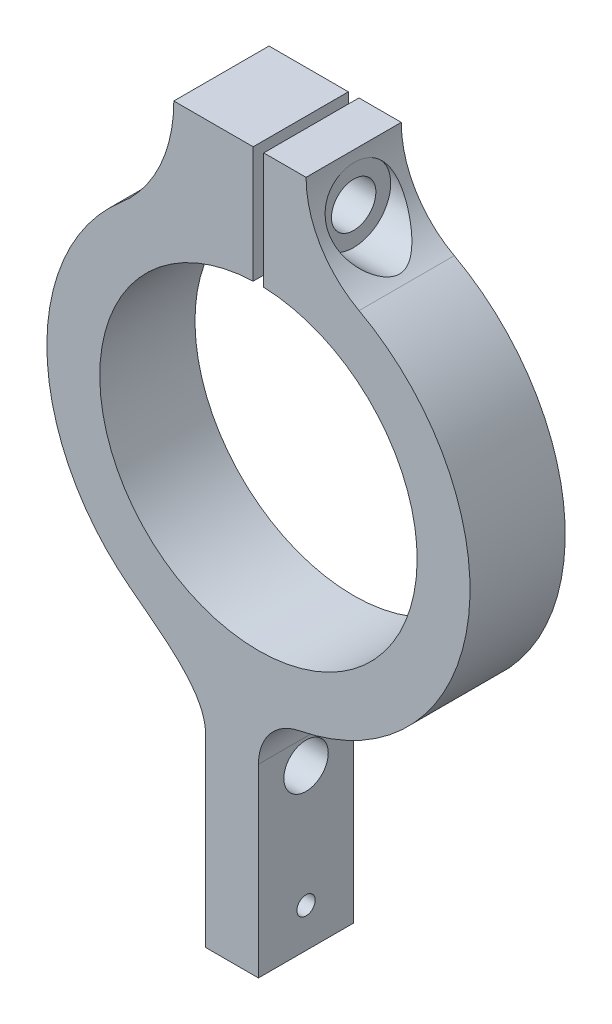
SolidWorks part; units mm, degrees
material "6061-T6 (SS)"
ref_plane "Front Plane" through (0, 0, 0) normal (0, 0, 1) x (1, 0, 0)
ref_plane "Top Plane" through (0, 0, 0) normal (0, 1, 0) x (1, 0, 0)
ref_plane "Right Plane" through (0, 0, 0) normal (1, 0, 0) x (0, 0, -1)
sketch "Sketch1" plane through (0, 0, 0) normal (0, 0, 1) x (1, 0, 0)
  line L0 (0, 0) -> (0, 40) construction
  line L1 (0, -48.6004) -> (0, -83.6004)
  line L2 (0, -83.6004) -> (-10, -83.6004)
  line L3 (-10, -83.6004) -> (-10, -48.6004)
  line L4 (30, 0) -> (40, 0) construction
  line L6 (0, 40) -> (0, 52) construction
  line L7 (0, 52) -> (1, 52) construction
  line L8 (1, 52) -> (1, 29.9833)
  line L9 (1, 52) -> (9, 52)
  line L11 (0, 52) -> (-1, 52) construction
  line L12 (-1, 52) -> (-1, 29.9833)
  line L13 (-1, 52) -> (-16, 52)
  arc A0 (-1, 29.9833) -> (1, 29.9833) centre (0, 0) ccw
  arc A1 (0, -48.6004) -> (7.6931, -39.2532) centre (9.525, -48.6004) cw
  arc A2 (0, 40) -> (-1, 39.9875) centre (0, 0) ccw construction
  arc A3 (9, 52) -> (19.0232, 35.1869) centre (28.1129, 52) ccw
  arc A4 (-25.9512, 30.439) -> (-26.5352, -29.9313) centre (0, 0) ccw
  circle A5 centre (0, 0) radius 40 construction
  arc A6 (-25.9512, 30.439) -> (-16, 52) centre (-44.3333, 52) ccw
  arc A8 (7.6931, -39.2532) -> (19.0232, 35.1869) centre (0, 0) ccw
  spline S0 degree 3 poles (-26.5352, -29.9313) (-20.9482, -34.8844) (-10, -40.904) (-10, -48.6004) knots 0 0 0 0 1 1 1 1
  point P27 (0, -40)
  dimension "D1" = 60
  dimension "D3" = 35
  dimension "D4" = 10
  dimension "D2" = 10
  dimension "D11" = 9.525
  dimension "D6" = 12
  dimension "D7" = 1
  dimension "D8" = 8
  dimension "D9" = 1
  dimension "D10" = 15
extrude "main body" add sketch "Sketch1" along normal blind 18
sketch "Sketch7" plane through (1, 0, 0) normal (-1, 0, 0) x (0, 0, 1)
  line L3 (9, 43) -> (9, 52) construction
  line L4 (18, 52) -> (0, 52) construction
  line L5 (9, 43) -> (0, 43) construction
  line L6 (0, 52) -> (0, 35.1869) construction
  circle A0 centre (9, 43) radius 4
  dimension "D1" = 8
sketch "Sketch12" plane through (0, 0, 0) normal (1, 0, 0) x (0, 0, -1)
  circle A0 centre (-9, -53.34) radius 4
  circle A1 centre (-9, -53.34) radius 7 construction
  circle A2 centre (-9, -76.2) radius 4
  circle A3 centre (-9, -76.2) radius 7 construction
  dimension "D1" = 8
  dimension "D2" = 14
  dimension "D3" = 14
  dimension "D4" = 8
  dimension "D6" = 22.86
  dimension "D5" = 76.2
hole_wizard "M8 Clearance Hole1" positions "Sketch13" profile "Sketch14" hole size "M8" standard "ANSI Metric"
sketch "Sketch13" plane through (1, 0, 0) normal (-1, 0, 0) x (0, 0, 1)
  point P0 (9, 43)
sketch "Sketch14" plane through (1, 43, 9) normal (0, 1, 0) x (0, 0, 1)
  line L0 (0, 0) -> (0, 39)
  line L1 (0, 39) -> (4.2, 39)
  line L2 (4.2, 39) -> (4.2, 0)
  line L5 (4.2, 0) -> (0, 0)
  line L11 (0, -6.35) -> (0, 107.95) construction
  dimension "Thru Hole Dia." = 8.4
  dimension "Thru Hole Depth" = 39
hole_wizard "M8 Clearance Hole2" positions "Sketch15" profile "Sketch16" hole size "M8" standard "ANSI Metric" end condition through all
sketch "Sketch15" plane through (1, 0, 0) normal (-1, 0, 0) x (0, 0, 1)
  point P0 (9, 43)
sketch "Sketch16" plane through (1, 43, 9) normal (0, 1, 0) x (0, 0, -1)
  line L0 (0, 0) -> (0, 41)
  line L1 (0, 41) -> (4.2, 41)
  line L2 (4.2, 41) -> (4.2, 0)
  line L5 (4.2, 0) -> (0, 0)
  line L11 (0, -6.35) -> (0, 107.95) construction
  dimension "Thru Hole Dia." = 8.4
  dimension "Thru Hole Depth" = 41
sketch "Sketch17" plane through (0, 0, 18) normal (0, 0, 1) x (1, 0, 0)
  line L0 (-16, 52) -> (-16, 25.3772)
  line L1 (9, 52) -> (9, 28.6182)
  arc A0 (-1, 29.9833) -> (1, 29.9833) centre (0, 0) ccw construction
hole_wizard "M8 Clearance Hole3" positions "Sketch18" profile "Sketch19" hole size "M8" standard "ANSI Metric" end condition through all
sketch "Sketch18" plane through (0, 0, 0) normal (1, 0, 0) x (0, 0, -1)
  point P0 (-9, -53.34)
sketch "Sketch19" plane through (0, -53.34, 9) normal (0, 1, 0) x (0, 0, -1)
  line L0 (0, 0) -> (0, 40)
  line L1 (0, 40) -> (4.2, 40)
  line L2 (4.2, 40) -> (4.2, 0)
  line L5 (4.2, 0) -> (0, 0)
  line L11 (0, -6.35) -> (0, 107.95) construction
  dimension "Thru Hole Dia." = 8.4
  dimension "Thru Hole Depth" = 40
ref_plane "Plane1" through (-16, 0, 0) normal (-1, 0, 0) x (0, 0, 1)
sketch "Sketch26" plane through (-16, 0, 0) normal (-1, 0, 0) x (0, 0, 1)
  circle A0 centre (9, 43) radius 7
  dimension "D1" = 14
ref_plane "Plane2" through (9, 0, 0) normal (1, 0, 0) x (0, 0, -1)
sketch "Sketch27" plane through (9, 0, 0) normal (1, 0, 0) x (0, 0, -1)
  circle A0 centre (-9, 43) radius 7
  circle A1 centre (-9, 43) radius 7 construction
extrude "Cut-Extrude2" cut sketch "Sketch27" along normal through all
sketch "Sketch29" plane through (0, 0, 18) normal (0, 0, 1) x (1, 0, 0)
  line L0 (-16, 52) -> (-42.54, 52) construction
  line L1 (-42.54, 52) -> (-42.54, 0) construction
  line L2 (-42.54, 0) -> (-40, 0) construction
  arc A0 (-25.9512, 30.439) -> (-26.5352, -29.9313) centre (0, 0) ccw construction
  dimension "D1" = 2.54
hole_wizard "#8-32 Tapped Hole1" positions "Sketch30" profile "Sketch32" tap size "#8-32" standard "ANSI Inch" end condition through all
sketch "Sketch30" plane through (0, 0, 0) normal (1, 0, 0) x (0, 0, -1)
  point P0 (-9, -76.2)
sketch "Sketch32" plane through (0, -76.2, 9) normal (0, 1, 0) x (0, 0, -1)
  line L0 (0, 0) -> (0, 40)
  line L1 (0, 40) -> (1.7272, 40)
  line L2 (1.7272, 40) -> (1.7272, 0)
  line L5 (1.7272, 0) -> (0, 0)
  line L11 (0, -6.35) -> (0, 107.95) construction
  dimension "Thru Tap Drill Dia." = 3.4544
  dimension "Thru Tap Drill Depth" = 40
cosmetic thread "Hole Thread1" parameters "D2"=4.1656
